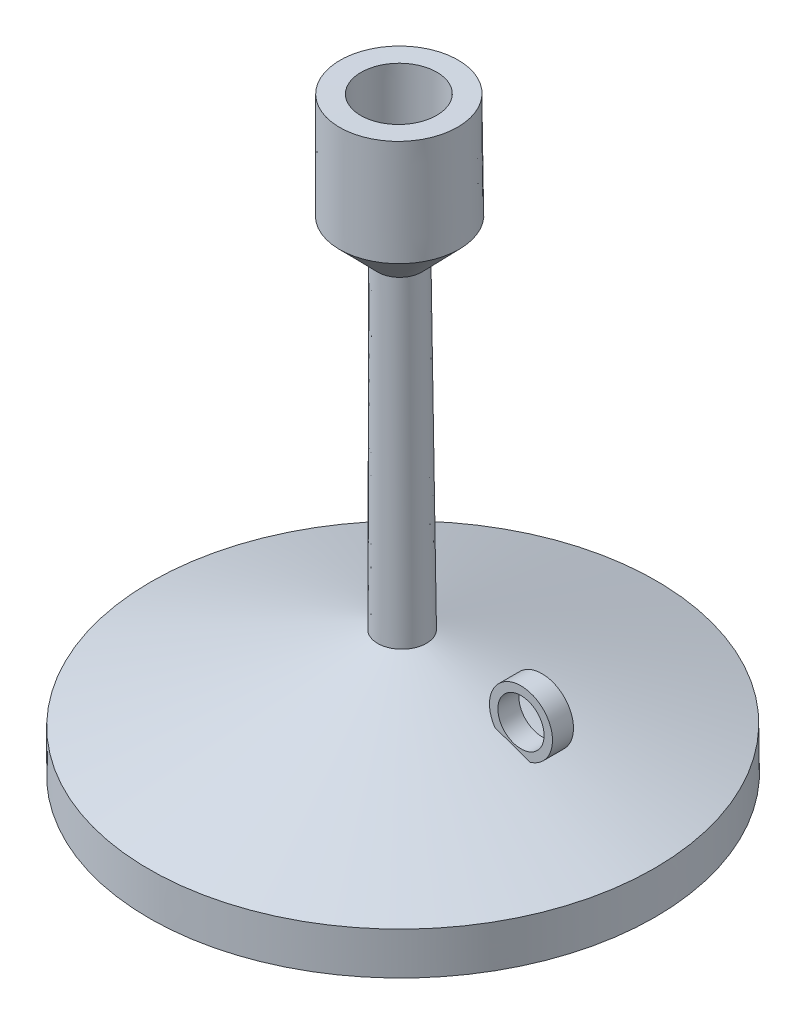
SolidWorks part; units mm, degrees
ref_plane "Front Plane" through (0, 0, 0) normal (0, 0, 1) x (1, 0, 0)
ref_plane "Top Plane" through (0, 0, 0) normal (0, 1, 0) x (1, 0, 0)
ref_plane "Right Plane" through (0, 0, 0) normal (1, 0, 0) x (0, 0, -1)
sketch "Sketch1" plane through (0, 0, 0) normal (0, 0, 1) x (1, 0, 0)
  line L0 (0, 0) -> (0, 140) construction
  line L1 (-0.8554, 120) -> (-10, 120)
  line L2 (-10, 120) -> (-10, 140)
  line L3 (-10, 140) -> (-15, 140)
  line L4 (-15, 140) -> (-15, 115)
  line L5 (-15, 115) -> (-6, 106)
  line L6 (-6, 106) -> (-6, 30)
  line L7 (-6, 30) -> (-60, 10)
  line L8 (-60, 10) -> (-60, 0)
  line L9 (-60, 0) -> (0, 0)
  line L10 (-0.8554, 120) -> (0, 0)
  dimension "D1" = 140
  dimension "D2" = 10
  dimension "D3" = 20
  dimension "D4" = 30
  dimension "D5" = 25
  dimension "D6" = 20
  dimension "D7" = 135
  dimension "D8" = 120
  dimension "D9" = 30
  dimension "D10" = 12
revolve "Revolve1" add sketch "Sketch1" angle 360 about L10
sketch "Sketch2" plane through (0, 0, 0) normal (0, 0, 1) x (1, 0, 0)
  line L0 (59.8513, 10.8543) -> (5.5717, 30.0825) construction
  line L1 (59.8513, 10.8543) -> (5.5717, 30.0825) construction
  circle A0 centre (30.5717, 27.5917) radius 7.5
  circle A1 centre (30.5717, 27.5917) radius 5.5
  point P4 (0, 0)
  dimension "D2" = 15
  dimension "D3" = 25
  dimension "D1" = 6
  dimension "D4" = 2
extrude "Boss-Extrude1" add sketch "Sketch2" along normal mid plane 5
